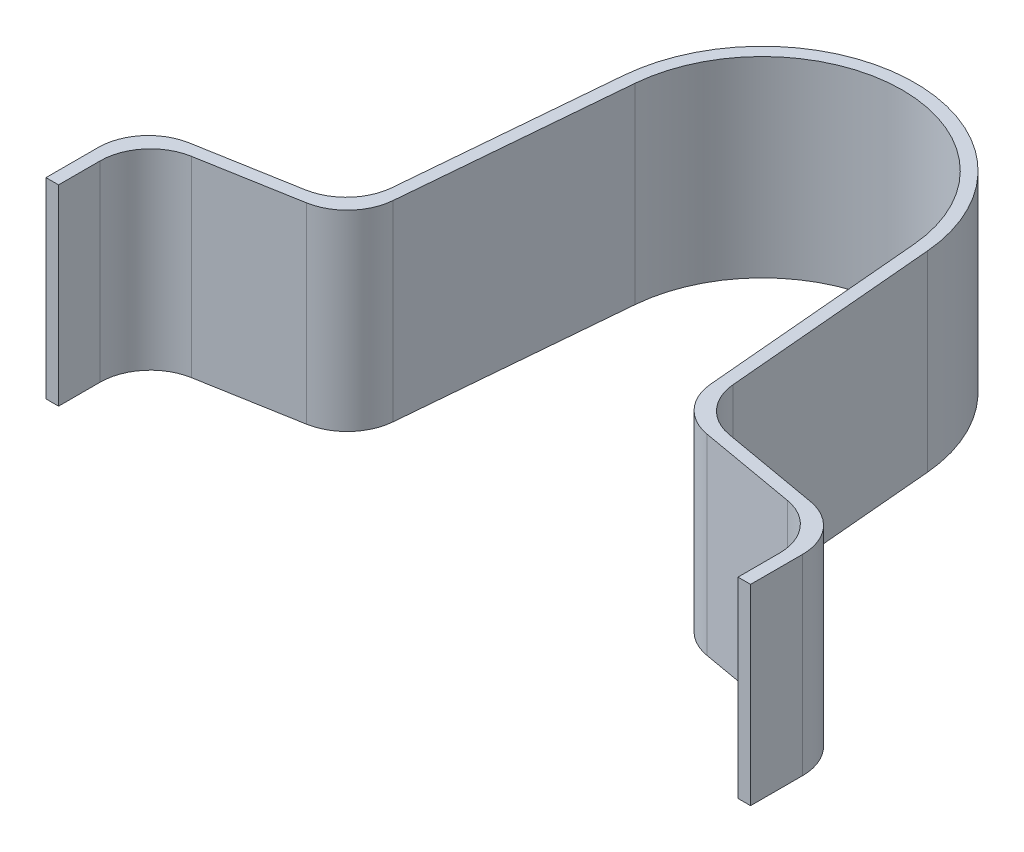
SolidWorks part; units mm, degrees
material "POLYURETHANE (11671)"
ref_plane "Front Plane" through (0, 0, 0) normal (0, 0, 1) x (1, 0, 0)
ref_plane "Top Plane" through (0, 0, 0) normal (0, 1, 0) x (1, 0, 0)
ref_plane "Right Plane" through (0, 0, 0) normal (1, 0, 0) x (0, 0, -1)
sketch "Sketch1" plane through (0, 0, 0) normal (0, 1, 0) x (1, 0, 0)
  line L1 (0, 0) -> (0, 22.2542) construction
  line L2 (0, 0) -> (26.0301, 0) construction
  line L3 (-22.1695, 1.937) -> (-27.3967, -57.8889)
  line L4 (-24.1619, 2.1111) -> (-22.1695, 1.937)
  line L5 (-24.1619, 2.1111) -> (-29.4043, -57.8889)
  line L11 (-29.4043, -57.8889) -> (-27.3967, -57.8889)
  line L13 (-22.1695, 1.937) -> (0, 0) construction
  line L14 (29.4043, -57.8889) -> (27.3967, -57.8889)
  line L15 (24.1619, 2.1111) -> (22.1695, 1.937)
  line L16 (24.1619, 2.1111) -> (29.4043, -57.8889)
  line L17 (22.1695, 1.937) -> (27.3967, -57.8889)
  circle A0 centre (0, 0) radius 24.254
  circle A1 centre (0, 0) radius 22.254
  dimension "D1" = 48.508
  dimension "D2" = 85.007
  dimension "D3" = 60
  dimension "D4" = 2
extrude "Boss-Extrude2" add sketch "Sketch1" along normal blind 30.48 contours A0 L5 L11 L3 | A1 L15 A0 L4 | L4 A0 L3 | L17 A0 L15
ref_plane "Plane1" through (0, 0, 35.3889) normal (0, 0, 1) x (1, 0, 0)
sketch "Sketch2" plane through (0, 30.48, 0) normal (0, 1, 0) x (1, 0, 0)
  line L0 (-27.4384, -35.3889) -> (-57.3749, -35.3889) construction
  line L1 (-24.1619, 2.1111) -> (-29.4043, -57.8889) construction
  line L2 (-29.4043, -57.8889) -> (-27.3967, -57.8889) construction
  line L3 (-27.6568, -37.8889) -> (-56.0133, -42.8889)
  line L4 (-56.0133, -42.8889) -> (-56.0133, -57.8889)
  line L5 (-56.0133, -57.8889) -> (-54.0133, -57.8889)
  line L6 (-54.0133, -57.8889) -> (-54.0133, -44.5671)
  line L7 (-54.0133, -44.5671) -> (-27.8371, -39.9515)
  line L8 (-27.8371, -39.9515) -> (-27.6568, -37.8889)
  line L9 (0, 0) -> (0, -90.906) construction
  line L10 (0, -55) -> (0, 55) construction
  line L11 (54.0133, -44.5671) -> (27.8371, -39.9515)
  line L12 (54.0133, -57.8889) -> (54.0133, -44.5671)
  line L13 (56.0133, -57.8889) -> (54.0133, -57.8889)
  line L14 (56.0133, -42.8889) -> (56.0133, -57.8889)
  line L15 (27.6568, -37.8889) -> (56.0133, -42.8889)
  line L16 (27.8371, -39.9515) -> (27.6568, -37.8889)
  dimension "D1" = 22.5
  dimension "D2" = 2
  dimension "D3" = 2
  dimension "D4" = 20
  dimension "D5" = 100
  dimension "D6" = 15
extrude "Boss-Extrude3" add sketch "Sketch2" against normal up to surface (30.48 mm away) up to face at (0, 0, 22.6249)
sketch "Sketch5" plane through (0, 30.48, 0) normal (0, 1, 0) x (1, 0, 0)
  line L0 (-27.8371, -39.9515) -> (0, -35.0431)
  line L1 (27.8371, -39.9515) -> (0, -35.0431)
  line L2 (-27.8371, -39.9515) -> (-29.4043, -57.8889)
  line L3 (27.8371, -39.9515) -> (29.4043, -57.8889)
  line L4 (-29.4043, -57.8889) -> (29.4043, -57.8889)
  line L18 (22.1695, 1.937) -> (27.3967, -57.8889)
  line L19 (27.3967, -57.8889) -> (29.4043, -57.8889)
  line L20 (29.4043, -57.8889) -> (27.8371, -39.9515)
  line L21 (27.8371, -39.9515) -> (54.0133, -44.5671)
  line L22 (54.0133, -44.5671) -> (54.0133, -57.8889)
  line L23 (54.0133, -57.8889) -> (56.0133, -57.8889)
  line L24 (56.0133, -57.8889) -> (56.0133, -42.8889)
  line L25 (56.0133, -42.8889) -> (27.6568, -37.8889)
  line L26 (27.6568, -37.8889) -> (24.1619, 2.1111)
  line L27 (-24.1619, 2.1111) -> (-27.6568, -37.8889)
  line L28 (-27.6568, -37.8889) -> (-56.0133, -42.8889)
  line L29 (-56.0133, -42.8889) -> (-56.0133, -57.8889)
  line L30 (-56.0133, -57.8889) -> (-54.0133, -57.8889)
  line L31 (-54.0133, -57.8889) -> (-54.0133, -44.5671)
  line L32 (-54.0133, -44.5671) -> (-27.8371, -39.9515)
  line L33 (-27.8371, -39.9515) -> (-29.4043, -57.8889)
  line L34 (-29.4043, -57.8889) -> (-27.3967, -57.8889)
  line L35 (-27.3967, -57.8889) -> (-22.1695, 1.937)
  line L36 (22.1695, 1.937) -> (27.3967, -57.8889)
  line L37 (27.3967, -57.8889) -> (29.4043, -57.8889)
  line L38 (29.4043, -57.8889) -> (27.8371, -39.9515)
  line L39 (27.8371, -39.9515) -> (54.0133, -44.5671)
  line L40 (54.0133, -44.5671) -> (54.0133, -57.8889)
  line L41 (54.0133, -57.8889) -> (56.0133, -57.8889)
  line L42 (56.0133, -57.8889) -> (56.0133, -42.8889)
  line L43 (56.0133, -42.8889) -> (27.6568, -37.8889)
  line L44 (27.6568, -37.8889) -> (24.1619, 2.1111)
  line L45 (-24.1619, 2.1111) -> (-27.6568, -37.8889)
  line L46 (-27.6568, -37.8889) -> (-56.0133, -42.8889)
  line L47 (-56.0133, -42.8889) -> (-56.0133, -57.8889)
  line L48 (-56.0133, -57.8889) -> (-54.0133, -57.8889)
  line L49 (-54.0133, -57.8889) -> (-54.0133, -44.5671)
  line L50 (-54.0133, -44.5671) -> (-27.8371, -39.9515)
  line L51 (-27.8371, -39.9515) -> (-29.4043, -57.8889)
  line L52 (-29.4043, -57.8889) -> (-27.3967, -57.8889)
  line L53 (-27.3967, -57.8889) -> (-22.1695, 1.937)
  arc A2 (24.1619, 2.1111) -> (-24.1619, 2.1111) centre (0, 0) ccw
  arc A3 (22.1695, 1.937) -> (-22.1695, 1.937) centre (0, 0) ccw
  arc A4 (24.1619, 2.1111) -> (-24.1619, 2.1111) centre (0, 0) ccw
  arc A5 (22.1695, 1.937) -> (-22.1695, 1.937) centre (0, 0) ccw
  line M23 (22.1695, 1.937) -> (27.3967, -57.8889)
  line M24 (27.3967, -57.8889) -> (29.4043, -57.8889)
  line M25 (29.4043, -57.8889) -> (27.8371, -39.9515)
  line M39 (-27.8371, -39.9515) -> (-29.4043, -57.8889)
  line M40 (-29.4043, -57.8889) -> (-27.3967, -57.8889)
  line M41 (-27.3967, -57.8889) -> (-22.1695, 1.937)
  dimension "D1" = 0
extrude "Cut-Extrude2" cut sketch "Sketch5" against normal through all contours L4 L1 L0 M41 M23 | L0 M39 M40 M41 | L1 M25 M23 M24
fillet "Fillet1" radius 8 8 edges at (54.0133, 15.24, 44.5671) (56.0133, 15.24, 42.8889) (-56.0133, 15.24, 42.8889) (-54.0133, 15.24, 44.5671) (25.798, 15.24, 39.592) (-25.798, 15.24, 39.592) (27.6568, 15.24, 37.8889) (-27.6568, 15.24, 37.8889)
